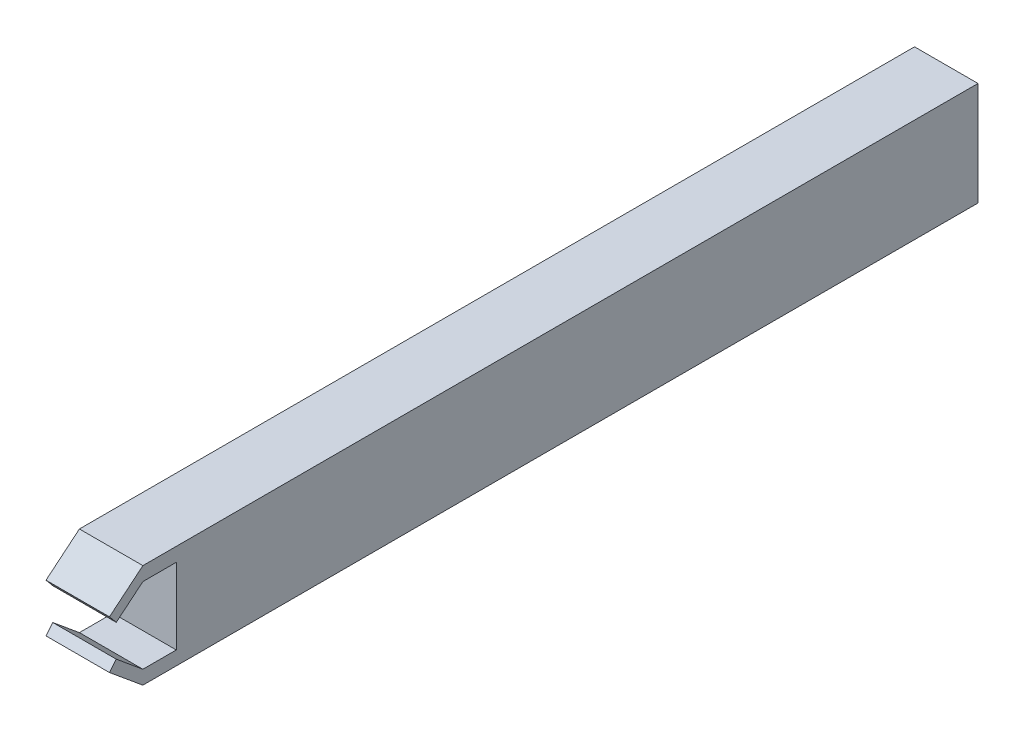
SolidWorks part; units mm, degrees
ref_plane "Front Plane" through (0, 0, 0) normal (0, 0, 1) x (1, 0, 0)
ref_plane "Top Plane" through (0, 0, 0) normal (0, 1, 0) x (1, 0, 0)
ref_plane "Right Plane" through (0, 0, 0) normal (1, 0, 0) x (0, 0, -1)
sketch "Sketch1" plane through (0, 0, 0) normal (0, 0, 1) x (1, 0, 0)
  line L1 (-9.5, -15.5) -> (9.5, -15.5)
  line L2 (-9.5, -15.5) -> (-9.5, 15.5)
  line L3 (-9.5, 15.5) -> (9.5, 15.5)
  line L4 (9.5, -15.5) -> (9.5, 15.5)
  line L5 (-9.5, -15.5) -> (9.5, 15.5) construction
  line L6 (-9.5, 15.5) -> (9.5, -15.5) construction
  point P0 (0, 0)
  dimension "D1" = 19
  dimension "D2" = 31
extrude "Boss-Extrude1" add sketch "Sketch1" along normal blind 240
sketch "Sketch2" plane through (-9.5, 0, 0) normal (-1, 0, 0) x (0, 0, 1)
  line L0 (240, 15.5) -> (250, 15.5)
  line L2 (250, 15.5) -> (260, 7.2265)
  line L3 (240, 11.3633) -> (250, 11.3633)
  line L4 (240, 15.5) -> (240, -15.5) construction
  line L5 (250, 11.3633) -> (257.9682, 4.7708)
  line L6 (257.9682, 4.7708) -> (260, 7.2265)
  line L7 (240, 15.5) -> (240, 11.3633)
  line L8 (240, 0) -> (286.8044, 0) construction
  line L9 (240, -15.5) -> (240, -11.3633)
  line L10 (257.9682, -4.7708) -> (260, -7.2265)
  line L11 (250, -11.3633) -> (257.9682, -4.7708)
  line L12 (240, -11.3633) -> (250, -11.3633)
  line L13 (250, -15.5) -> (260, -7.2265)
  line L15 (240, -15.5) -> (250, -15.5)
  dimension "D1" = 10
  dimension "D2" = 10
  dimension "D3" = 219.602
  dimension "D4" = 3.1873
  dimension "D5" = 7.9682
extrude "Boss-Extrude2" add sketch "Sketch2" against normal up to surface (19 mm away) up to face at (9.5, 0, 120)
